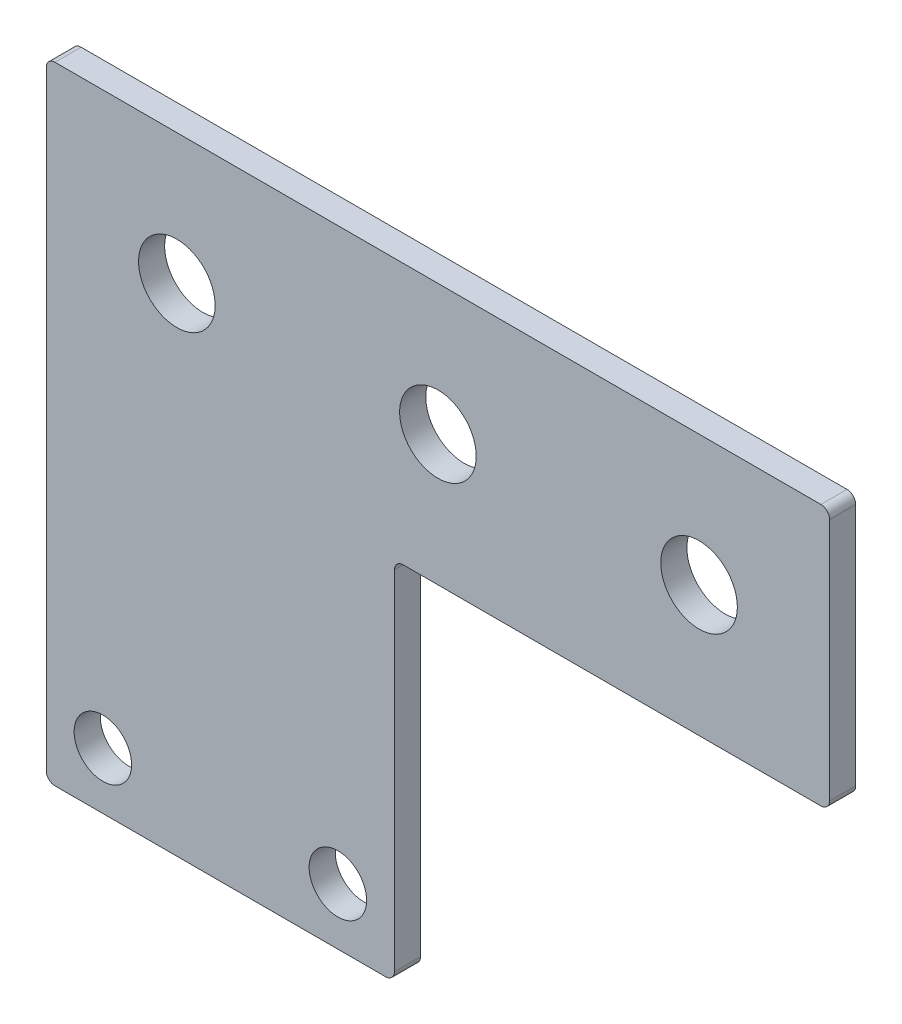
SolidWorks part; units mm, degrees
ref_plane "前视基准面" through (0, 0, 0) normal (0, 0, 1) x (1, 0, 0)
ref_plane "上视基准面" through (0, 0, 0) normal (0, 1, 0) x (1, 0, 0)
ref_plane "右视基准面" through (0, 0, 0) normal (1, 0, 0) x (0, 0, -1)
other "Configuration Table"
sketch "草图1" plane through (0, 0, 0) normal (0, 0, 1) x (1, 0, 0)
  line L0 (0, 0) -> (0, -72)
  line L1 (0, -72) -> (40, -72)
  line L2 (40, -72) -> (40, -30)
  line L3 (40, -30) -> (90, -30)
  line L4 (90, -30) -> (90, 0)
  line L5 (90, 0) -> (0, 0)
  line L6 (20, -72) -> (20, -65.5)
  line L7 (20, -65.5) -> (33.5, -65.5)
  line L8 (90, -15) -> (0, -15)
  circle A0 centre (33.5, -65.5) radius 3.3
  circle A1 centre (6.5, -65.5) radius 3.3
  circle A2 centre (45, -15) radius 4.4
  circle A3 centre (75, -15) radius 4.4
  circle A4 centre (15, -15) radius 4.4
  dimension "D1" = 27
  dimension "D7" = 6.6
  dimension "D8" = 30
  dimension "D10" = 8.8
  dimension "D2" = 40
  dimension "D3" = 90
  dimension "D4" = 42
  dimension "D5" = 30
  dimension "D6" = 6.5
  dimension "D9" = 30
extrude "凸台-拉伸1" add sketch "草图1" along normal blind 3
fillet "圆角1" radius 1 6 edges at (40, -72, 1.5) (0, -72, 1.5) (0, 0, 1.5) (90, 0, 1.5) (90, -30, 1.5) (40, -30, 1.5)
